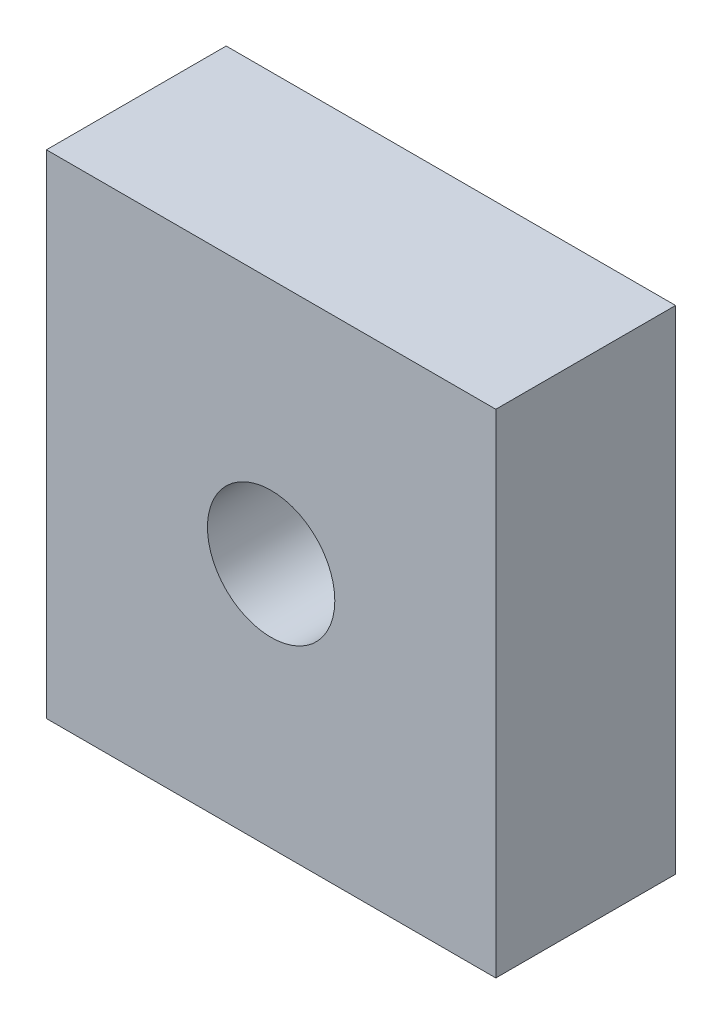
SolidWorks part; units mm, degrees
material "Balsa"
ref_plane "Front Plane" through (0, 0, 0) normal (0, 0, 1) x (1, 0, 0)
ref_plane "Top Plane" through (0, 0, 0) normal (0, 1, 0) x (1, 0, 0)
ref_plane "Right Plane" through (0, 0, 0) normal (1, 0, 0) x (0, 0, -1)
sketch "Sketch1" plane through (0, 0, 0) normal (0, 0, 1) x (1, 0, 0)
  line L1 (0, 0) -> (-15.875, 0)
  line L2 (0, 0) -> (0, 17.4)
  line L3 (0, 17.4) -> (-15.875, 17.4)
  line L4 (-15.875, 0) -> (-15.875, 17.4)
  dimension "D1" = 17.4
  dimension "D2" = 15.875
extrude "Boss-Extrude1" add sketch "Sketch1" along normal blind 6.35
hole_wizard "M4 Clearance Hole1" positions "Sketch3" profile "Sketch2" hole size "M4" standard "Ansi Metric"
sketch "Sketch3" plane through (0, 0, 6.35) normal (0, 0, 1) x (1, 0, 0)
  line L0 (-7.9375, 8.7) -> (-7.9375, 17.4) construction
  line L1 (0, 17.4) -> (-15.875, 17.4) construction
  line L3 (-7.9375, 8.7) -> (-15.875, 8.7) construction
  line L4 (-15.875, 17.4) -> (-15.875, 0) construction
  point P0 (-7.9375, 8.7)
sketch "Sketch2" plane through (-7.9375, 8.7, 6.35) normal (1, 0, 0) x (0, -1, 0)
  line L0 (0, 0) -> (0, 14.0519)
  line L1 (0, 14.0519) -> (2.25, 12.7)
  line L2 (2.25, 12.7) -> (2.25, 0)
  line L5 (2.25, 0) -> (0, 0)
  line L10 (0, 14.0519) -> (-2.25, 12.7) construction
  line L11 (0, -6.35) -> (0, 107.95) construction
  dimension "Hole Dia." = 4.5
  dimension "Hole Depth" = 12.7
  dimension "Drill Angle" = 118
